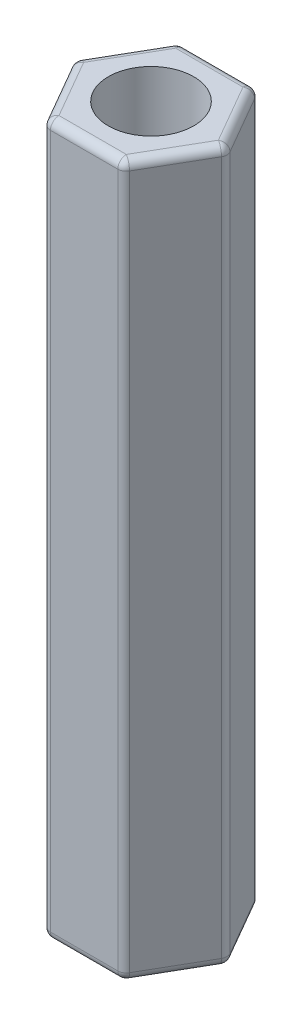
SolidWorks part; units mm, degrees
ref_plane "前视基准面" through (0, 0, 0) normal (0, 0, 1) x (1, 0, 0)
ref_plane "上视基准面" through (0, 0, 0) normal (0, 1, 0) x (1, 0, 0)
ref_plane "右视基准面" through (0, 0, 0) normal (1, 0, 0) x (0, 0, -1)
sketch "草图1" plane through (0, 0, 0) normal (0, 1, 0) x (1, 0, 0)
  line L1 (2.7135, 0) -> (1.3568, 2.35)
  line L2 (1.3568, 2.35) -> (-1.3568, 2.35)
  line L3 (-1.3568, 2.35) -> (-2.7135, 0)
  line L4 (-2.7135, 0) -> (-1.3568, -2.35)
  line L5 (-1.3568, -2.35) -> (1.3568, -2.35)
  line L6 (1.3568, -2.35) -> (2.7135, 0)
  circle A0 centre (0, 0) radius 2.35 construction
  circle A1 centre (0, 0) radius 1.5
  dimension "D1" = 4.7
extrude "凸台-拉伸1" add sketch "草图1" along normal blind 25
fillet "圆角1" radius 0.3 18 edges at (2.7135, 12.5, 0) (1.3568, 12.5, -2.35) (-1.3568, 12.5, -2.35) (-2.7135, 12.5, 0) (-1.3568, 12.5, 2.35) (1.3568, 12.5, 2.35) (0, 25, 2.35) (-2.0352, 25, 1.175) (-2.0352, 25, -1.175) (0, 25, -2.35) (2.0352, 25, -1.175) (2.0352, 25, 1.175) (0, 0, 2.35) (-2.0352, 0, 1.175) (-2.0352, 0, -1.175) (0, 0, -2.35) (2.0352, 0, -1.175) (2.0352, 0, 1.175)
